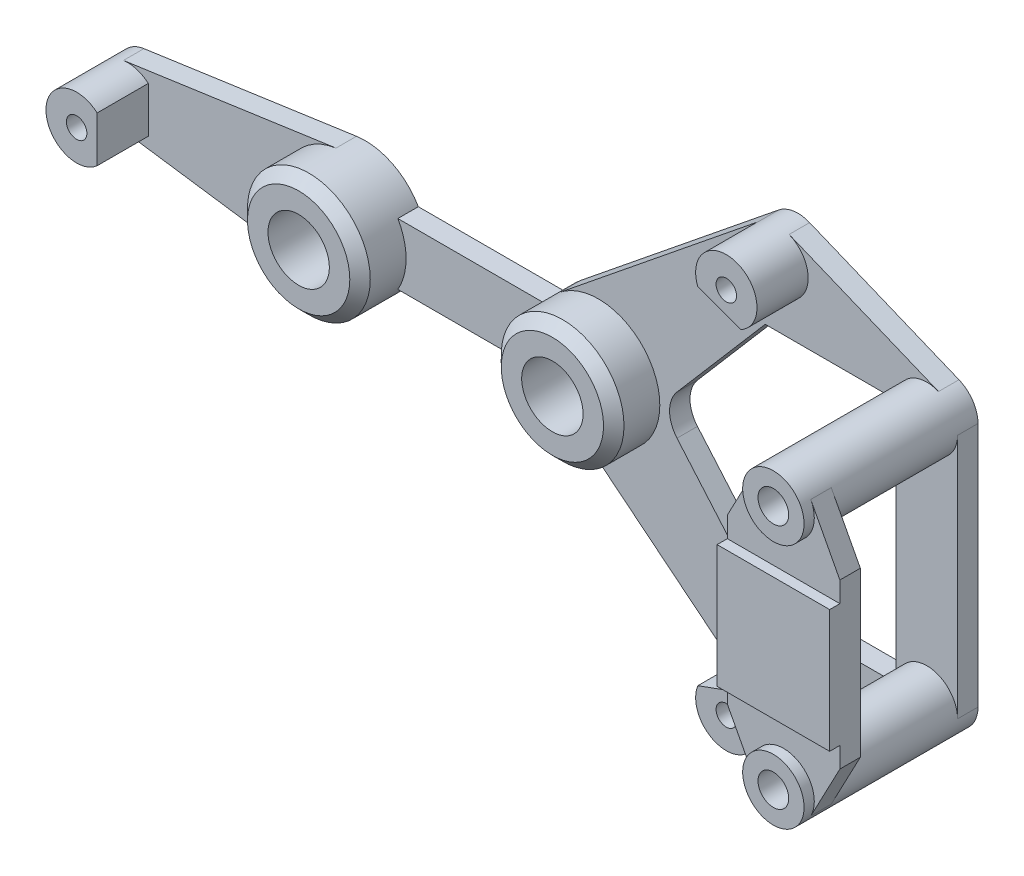
SolidWorks part; units mm, degrees
ref_plane "Front Plane" through (0, 0, 0) normal (0, 0, 1) x (1, 0, 0)
ref_plane "Top Plane" through (0, 0, 0) normal (0, 1, 0) x (1, 0, 0)
ref_plane "Right Plane" through (0, 0, 0) normal (1, 0, 0) x (0, 0, -1)
sketch "Sketch1" plane through (0, 0, 0) normal (0, 0, 1) x (1, 0, 0)
  line L0 (-24.8, 0) -> (0, 0) construction
  line L1 (-5.1962, 3) -> (-19.6038, 3)
  line L2 (-5.1962, -3) -> (-19.6038, -3)
  line L3 (-46, 0) -> (-24.8, 0) construction
  line L4 (0, 0) -> (0, 18) construction
  line L5 (0, 18) -> (17.5, 18) construction
  line L6 (-46.4245, -2.9698) -> (-25.6491, -5.9396)
  line L7 (-46.4245, 2.9698) -> (-25.6491, 5.9396)
  line L8 (-3.7713, 4.6666) -> (15.6143, 20.3333)
  line L9 (7.6778, 1.9542) -> (16.3027, 12)
  line L10 (7.6778, -1.9542) -> (16.3027, -12)
  line L11 (-3.7713, -4.6666) -> (15.6143, -20.3333)
  line L12 (0, 0) -> (32.1, 0) construction
  line L13 (32.1, -12) -> (32.1, 12) construction
  line L14 (32.1, 12) -> (32.1, -12) construction
  line L15 (35.1, 12) -> (35.1, -12)
  line L16 (29.1, 12) -> (29.1, -12)
  line L17 (16.3027, -12) -> (29.1, -12)
  line L18 (18.6403, -20.7748) -> (33.2403, -14.7748)
  line L19 (29.1, 0) -> (35.1, 0) construction
  line L20 (29.1, 12) -> (16.3027, 12)
  line L21 (18.6403, 20.7748) -> (33.2403, 14.7748)
  arc A0 (-5.1962, -3) -> (-3.7713, -4.6666) centre (0, 0) ccw
  arc A2 (-19.6038, 3) -> (-25.6491, 5.9396) centre (-24.8, 0) ccw
  arc A3 (-46.4245, 2.9698) -> (-46.4245, -2.9698) centre (-46, 0) ccw
  arc A4 (18.6403, 20.7748) -> (15.6143, 20.3333) centre (17.5, 18) ccw
  arc A5 (18.6403, -20.7748) -> (15.6143, -20.3333) centre (17.5, -18) cw
  arc A7 (-3.7713, 4.6666) -> (-5.1962, 3) centre (0, 0) ccw
  arc A8 (7.6778, 1.9542) -> (7.6778, -1.9542) centre (9.954, 0) ccw
  arc A9 (-25.6491, -5.9396) -> (-19.6038, -3) centre (-24.8, 0) ccw
  arc A11 (35.1, 12) -> (33.2403, 14.7748) centre (32.1, 12) ccw
  arc A12 (33.2403, -14.7748) -> (35.1, -12) centre (32.1, -12) ccw
  point P9 (32.1, 0)
  point P26 (6, 0)
  point P29 (32.1, 0)
  dimension "D2" = 12
  dimension "D4" = 6
  dimension "D9" = 3
  dimension "D12" = 3
  dimension "D1" = 24.8
  dimension "D3" = 6
  dimension "D5" = 21.2
  dimension "D6" = 18
  dimension "D7" = 17.5
  dimension "D8" = 6
  dimension "D10" = 24
  dimension "D11" = 32.1
extrude "Boss-Extrude1" add sketch "Sketch1" against normal blind 2
sketch "Sketch2" plane through (0, 0, 0) normal (0, 0, 1) x (1, 0, 0)
  circle A0 centre (-24.8, 0) radius 6
  circle A1 centre (0, 0) radius 6
  circle A2 centre (-24.8, 0) radius 3
  circle A3 centre (0, 0) radius 3
  dimension "D1" = 6
extrude "Boss-Extrude2" add sketch "Sketch2" along normal blind 4.5
chamfer "Chamfer1" distance 1 angle 45 2 edges at (6, 0, 4.5) (-18.8, 0, 4.5)
sketch "Sketch3" plane through (0, 0, 0) normal (0, 0, 1) x (1, 0, 0)
  line L0 (-44, -2.2361) -> (-44, 2.2361)
  line L1 (14.7147, -16.8854) -> (18.9172, -15.3558)
  line L2 (0, 0) -> (23.4915, 0) construction
  line L3 (14.7147, 16.8854) -> (18.9172, 15.3558)
  arc A0 (-44, 2.2361) -> (-44, -2.2361) centre (-46, 0) ccw
  arc A1 (18.9172, 15.3558) -> (14.7147, 16.8854) centre (17.5, 18) ccw
  arc A2 (14.7147, -16.8854) -> (18.9172, -15.3558) centre (17.5, -18) ccw
  circle A3 centre (17.5, -18) radius 1
  circle A4 centre (17.5, 18) radius 1
  circle A5 centre (-46, 0) radius 1
  dimension "D1" = 2
  dimension "D2" = 2
  dimension "D3" = 20
  dimension "D4" = 2
extrude "Boss-Extrude3" add sketch "Sketch3" along normal blind 5
sketch "Sketch4" plane through (0, 0, 0) normal (0, 0, 1) x (1, 0, 0)
  circle A0 centre (32.1, -12) radius 3
  circle A1 centre (32.1, 12) radius 3
  circle A2 centre (32.1, -12) radius 1.5
  circle A3 centre (32.1, 12) radius 1.5
  dimension "D1" = 3
extrude "Boss-Extrude4" add sketch "Sketch4" along normal blind 15
sketch "Sketch5" plane through (0, 0, 15) normal (0, 0, 1) x (1, 0, 0)
  line L0 (32.1, 12) -> (32.1, -12) construction
  line L1 (29.4462, -13.399) -> (26.6, -8)
  line L2 (26.6, 8) -> (37.6, 8) construction
  line L3 (26.6, 8) -> (26.6, -8)
  line L4 (26.6, -8) -> (37.6, -8) construction
  line L5 (37.6, 8) -> (37.6, -8)
  line L6 (26.6, 8) -> (37.6, -8) construction
  line L7 (26.6, -8) -> (37.6, 8) construction
  line L8 (34.7538, -13.399) -> (37.6, -8)
  line L9 (32.1, 0) -> (37.6, 0) construction
  line L10 (34.7538, 13.399) -> (37.6, 8)
  line L11 (29.4462, 13.399) -> (26.6, 8)
  circle A0 centre (32.1, -12) radius 1.5 construction
  circle A1 centre (32.1, -12) radius 3 construction
  circle A2 centre (32.1, 12) radius 3 construction
  circle A3 centre (32.1, 12) radius 1.5 construction
  circle A4 centre (32.1, -12) radius 1.5
  arc A5 (29.4462, -13.399) -> (34.7538, -13.399) centre (32.1, -12) ccw
  arc A6 (34.7538, 13.399) -> (29.4462, 13.399) centre (32.1, 12) ccw
  circle A7 centre (32.1, 12) radius 1.5
  point P12 (32.1, 0)
  dimension "D1" = 11
  dimension "D2" = 16
extrude "Boss-Extrude5" add sketch "Sketch5" against normal blind 3
sketch "Sketch6" plane through (0, 0, 15) normal (0, 0, 1) x (1, 0, 0)
  line L0 (29.4462, 13.399) -> (26.6, 8) construction
  line L1 (37.6, 8) -> (34.7538, 13.399) construction
  line L2 (29.4462, 13.399) -> (26.6, 8)
  line L3 (37.6, 8) -> (34.7538, 13.399)
  line L4 (26.6, -8) -> (29.4462, -13.399) construction
  line L5 (34.7538, -13.399) -> (37.6, -8) construction
  line L6 (37.6, -8) -> (37.6, 8) construction
  line L7 (26.6, 8) -> (26.6, -8) construction
  line L8 (26.6, -8) -> (29.4462, -13.399)
  line L9 (34.7538, -13.399) -> (37.6, -8)
  line L10 (37.6, -8) -> (37.6, -6)
  line L11 (26.6, 8) -> (26.6, 6)
  line L12 (37.6, 6) -> (26.6, 6)
  line L13 (37.6, -6) -> (26.6, -6)
  line L14 (26.6, -6) -> (26.6, -8)
  line L15 (37.6, 6) -> (37.6, 8)
  arc A0 (29.4462, 13.399) -> (34.7538, 13.399) centre (32.1, 12) ccw
  arc A1 (34.7538, -13.399) -> (29.4462, -13.399) centre (32.1, -12) ccw
  dimension "D1" = 12
extrude "Cut-Extrude1" cut sketch "Sketch6" against normal blind 1
